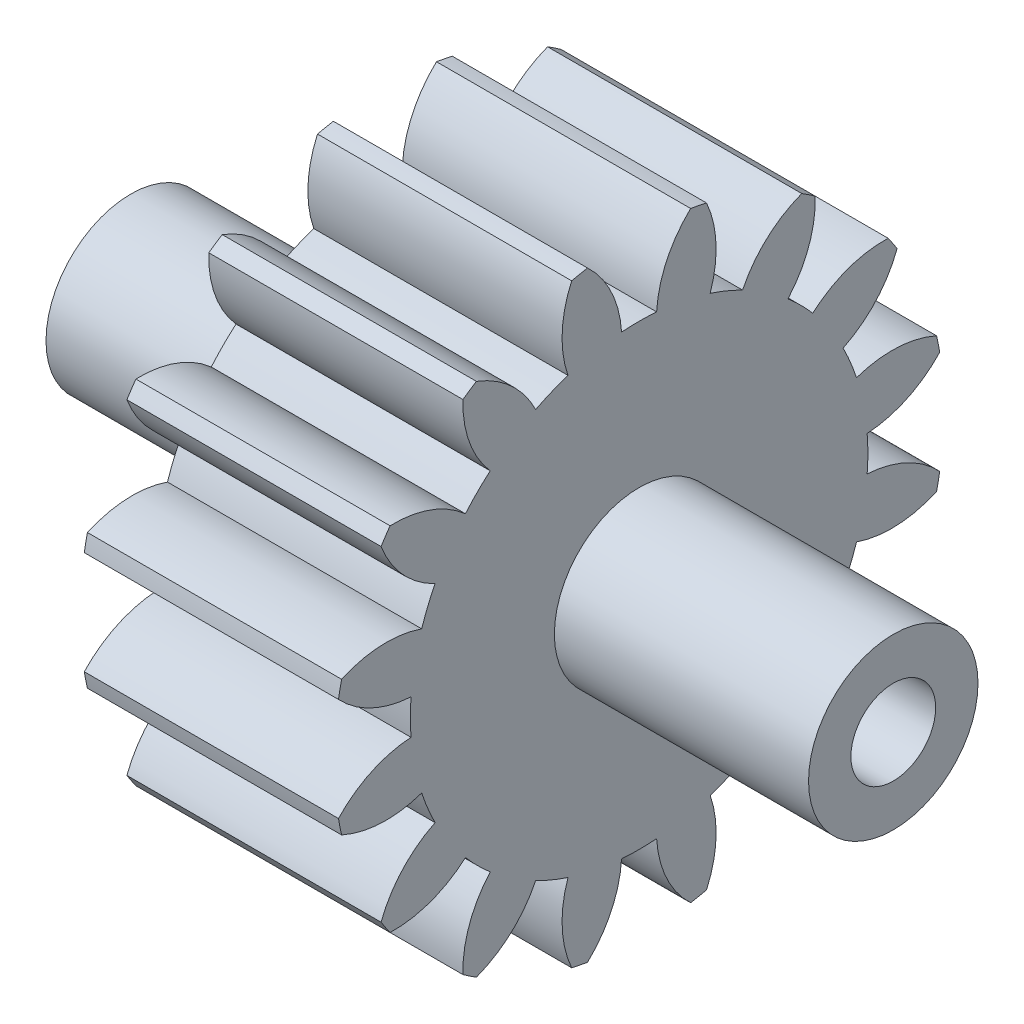
SolidWorks part; units mm, degrees
ref_plane "Plane1" through (0, 0, 0) normal (0, 0, 1) x (1, 0, 0)
ref_plane "Plane2" through (0, 0, 0) normal (0, 1, 0) x (1, 0, 0)
ref_plane "Plane3" through (0, 0, 0) normal (1, 0, 0) x (0, 0, -1)
other "Configuration Table"
sketch "HoldingSke" plane through (0, 0, 0) normal (0, 1, 0) x (1, 0, 0)
  line L0 (0, 0) -> (0.4806, -0.1378)
  line L1 (-15, 0) -> (100, 0) construction
  line L2 (0, 0) -> (-2.1039, 2.3779)
  line L3 (0, 0) -> (-11.863, 4.5341)
  line L4 (0, 0) -> (8.3015, 2.3804)
  line L5 (0, 0) -> (-42.1629, -15.7255)
  line L6 (0, 0) -> (-12.4344, -8.3896)
  line L7 (-2.1039, 2.3779) -> (7.5823, 46.3231)
  line L8 (-76.2, 54.61) -> (-75.3, 54.61)
  line L9 (-71.009, 38.7566) -> (-53.1078, 45.2721)
  line L10 (-76.2, 71.12) -> (104.1128, 71.12)
  line L11 (0, 0) -> (-15, 0)
  line L12 (-76.2, 101.6) -> (-76.133, 101.6)
  line L13 (24.9733, 27.94) -> (52.9518, 28.4284)
  line L14 (24.9733, 27.94) -> (24.9743, 27.94)
  line L15 (24.9733, 27.94) -> (100.4006, 29.5858)
  line L16 (-63.627, -2) -> (-12.827, -2)
  circle A0 centre (0, 0) radius 2.5
  circle A1 centre (0, 0) radius 5
  circle A2 centre (0, 0) radius 5
  circle A3 centre (0, 0) radius 2.5
  dimension "MHD" = 10
  dimension "Hub_dia" = 10
  dimension "Bore" = 5
  dimension "MBD" = 5
  dimension "Num_teeth" = 16
  dimension "Pitch" = 0.5
  dimension "Overall_len" = 45
  dimension "Show_teeth" = 16
  dimension "Thickness" = 15
  dimension "OAL" = 45.0001
  dimension "T_dim" = 0.9
  dimension "Ap" = 20
  dimension "H" = 19.05
  dimension "Pitch_radius" = 180.3128
  dimension "Width" = 15
  dimension "Backlash" = 0.067
  dimension "Addendum_fac" = 1
  dimension "Dedendum_fac" = 1.25
  dimension "Clearance_fac" = 0.25
  dimension "Dedendum_add" = 0.001
  dimension "Module" = 2
sketch "BasProSke" plane through (0, 0, 0) normal (0, 1, 0) x (1, 0, 0)
  line L0 (-10, 0) -> (60, 0) construction
  line L1 (0, 0) -> (0, 18)
  line L2 (0, 0) -> (15, 0)
  line L3 (15, 0) -> (15, 18)
  line L4 (15, 18) -> (0, 18)
  dimension "Thickness" = 15
  dimension "Diameter" = 36
revolve "Base-Revolve" add sketch "BasProSke" angle 360 about L0
sketch "TooCutSke" plane through (0, 0, 0) normal (1, 0, 0) x (0, 0, -1)
  line L1 (0, 0) -> (0, 107) construction
  line L2 (0, 0) -> (-1.6854, 15.911) construction
  line L3 (0, 0) -> (-6.2172, 31.2558) construction
  line L4 (-1.6854, 15.911) -> (-3.1086, 15.6279) construction
  arc A0 (1.0343, 13.4593) -> (-1.0343, 13.4593) centre (0, 0) ccw
  arc A1 (3.0657, 17.7628) -> (-3.0657, 17.7628) centre (0, 0) ccw
  circle A2 centre (0, 0) radius 16 construction
  circle A3 centre (0, 0) radius 15.0351 construction
  arc A4 (-1.0343, 13.4593) -> (-3.0657, 17.7628) centre (-7.4228, 13.075) ccw
  arc A5 (3.0657, 17.7628) -> (1.0343, 13.4593) centre (7.4228, 13.075) ccw
  dimension "Root_dia" = 26.998
  dimension "Overcut_dia" = 36.0508
  dimension "Pitch_dia" = 32
  dimension "Base_dia" = 30.0702
  dimension "Flank_rad" = 6.4
  dimension "Half_ang" = 11.25
  dimension "Half_CT" = 1.451
extrude "ToothCut" cut sketch "TooCutSke" along normal through all
fillet "Breaks" [suppressed] radius 0.04
fillet "RootFillets" [suppressed] radius 0.501
pattern_circular "TeethCuts" count 16 every 22.5 about axis through (-10, 0, 0) along (1, 0, 0) of "ToothCut", "RootFillets", "Breaks"
sketch "HubNeaOneSke" plane through (0, 0, 0) normal (-1, 0, 0) x (0, 0, 1)
  circle A0 centre (0, 0) radius 5
  dimension "Diameter" = 10
extrude "HubNearOne" [suppressed] add sketch "HubNeaOneSke" along normal blind 30.0001
sketch "HubNeaBotSke" plane through (0, 0, 0) normal (-1, 0, 0) x (0, 0, 1)
  circle A0 centre (0, 0) radius 5
  dimension "Diameter" = 10
extrude "HubNearBoth" add sketch "HubNeaBotSke" along normal blind 15
ref_plane "FarPln" through (15, 0, 0) normal (1, 0, 0) x (0, 0, -1)
sketch "HubFarSke" plane through (15, 0, 0) normal (1, 0, 0) x (0, 0, -1)
  circle A0 centre (0, 0) radius 5
  dimension "Diameter" = 10
extrude "HubFar" add sketch "HubFarSke" along normal blind 15
sketch "BorSke" plane through (0, 0, 0) normal (1, 0, 0) x (0, 0, -1)
  circle A0 centre (0, 0) radius 2.5
  dimension "Diameter" = 5
extrude "Bore" cut sketch "BorSke" along normal mid plane 90.0001
sketch "KeySke" plane through (0, 0, 0) normal (1, 0, 0) x (0, 0, -1)
  line L0 (-1, 0) -> (-1, 3.4)
  line L1 (-1, 3.4) -> (1, 3.4)
  line L2 (1, 3.4) -> (1, 0)
  line L3 (0, 0) -> (0, 34) construction
  line L4 (-1, 0) -> (1, 0)
  dimension "Offset" = 3.4
  dimension "Width" = 2
extrude "Keyway" [suppressed] cut sketch "KeySke" along normal mid plane 90.0001
pattern_circular "Keyway2" [suppressed] count 2 every 90 about axis through (-10, 0, 0) along (1, 0, 0)
equation "' \"Module@HoldingSke\" = 6.35"
equation "' \"Num_teeth@HoldingSke\" = 12"
equation "' \"Ap@HoldingSke\" =  20"
equation "' \"Ap@HoldingSke\" = 20"
equation "' \"Width@HoldingSke\" = 0.5 * 25.4"
equation "' \"Hub_dia@HoldingSke\"= 1 * 25.4"
equation "' \"Hub_dia@HoldingSke\" = 1 * 25.4"
equation "' \"Overall_len@HoldingSke\" = 1.0 * 25.4"
equation "' \"Bore@HoldingSke\" = 0.75 * 25.4"
equation "' \"T_dim@HoldingSke\" = 0.1 * 25.4"
equation "' \"Width@KeySke\" = 0.25 * 25.4"
equation "' \"Show_teeth@HoldingSke\" = 13"
equation "' \"Backlash@HoldingSke\" = 0.009 * 25.4"
equation "' \"Addendum_fac@HoldingSke\" = 1.0"
equation "' \"Dedendum_fac@HoldingSke\" = 1.25"
equation "' \"Dedendum_add@HoldingSke\" = 0.00005 * 25.4"
equation "' \"Clearance_fac@HoldingSke\" = 0.25"
equation "\"Pitch@HoldingSke\" = 1 / \"Module@HoldingSke\""
equation "\"Overcut_dia@TooCutSke\" = (\"Num_teeth@HoldingSke\" + 2 * \"Addendum_fac@HoldingSke\") / \"Pitch@HoldingSke\" + 0.002 * 25.4"
equation "\"Pitch_dia@TooCutSke\" = \"Num_teeth@HoldingSke\" / \"Pitch@HoldingSke\""
equation "\"Base_dia@TooCutSke\" = \"Num_teeth@HoldingSke\" / \"Pitch@HoldingSke\" * cos((\"Ap@HoldingSke\"  * 3.14159265 / 180))"
equation "\"Root_dia@TooCutSke\" = (\"Num_teeth@HoldingSke\" + 2) / \"Pitch@HoldingSke\" - 2 * (\"Addendum_fac@HoldingSke\" + \"Dedendum_fac@HoldingSke\") / \"Pitch@HoldingSke\" - \"Dedendum_add@HoldingSke\" * 2"
equation "\"Half_ang@TooCutSke\" = 180 / \"Num_teeth@HoldingSke\""
equation "\"Half_CT@TooCutSke\" = \"Num_teeth@HoldingSke\" / \"Pitch@HoldingSke\" * sin((3.14159265 / 2 / \"Num_teeth@HoldingSke\")) / 2 - 7 * \"Backlash@HoldingSke\" / 4"
equation "\"Flank_rad@TooCutSke\" = \"Num_teeth@HoldingSke\" / \"Pitch@HoldingSke\" / 5"
equation "\"Radius@RootFillets\" = \"Clearance_fac@HoldingSke\" / \"Pitch@HoldingSke\" + \"Dedendum_add@HoldingSke\""
equation "\"Break_rad@Breaks\" = 0.02 / \"Pitch@HoldingSke\""
equation "\"Thickness@HoldingSke\" = \"Width@HoldingSke\""
equation "\"OAL@HoldingSke\" = \"Thickness@HoldingSke\""
equation "\"MHD@HoldingSke\" = (\"Num_teeth@HoldingSke\" + 2) / \"Pitch@HoldingSke\" - 2 * (\"Addendum_fac@HoldingSke\" + \"Dedendum_fac@HoldingSke\")  / \"Pitch@HoldingSke\" - \"Dedendum_add@HoldingSke\" * 2"
equation "\"MBD@HoldingSke\" = (\"Num_teeth@HoldingSke\" + 2) / \"Pitch@HoldingSke\" - 2 * (\"Addendum_fac@HoldingSke\" + \"Dedendum_fac@HoldingSke\")  / \"Pitch@HoldingSke\" - \"Dedendum_add@HoldingSke\" * 2 - 0.002 * 25.4"
equation "\"MHD@HoldingSke\" = ((sgn( \"MHD@HoldingSke\" - \"Hub_dia@HoldingSke\" )-1)*( \"MHD@HoldingSke\" - \"Hub_dia@HoldingSke\" ))/-2+ \"Hub_dia@HoldingSke\""
equation "\"MBD@HoldingSke\" = ((sgn( \"MBD@HoldingSke\" - \"Bore@HoldingSke\" )-1)*( \"MBD@HoldingSke\" - \"Bore@HoldingSke\" ))/-2+ \"Bore@HoldingSke\""
equation "\"OAL@HoldingSke\" = ((sgn( \"OAL@HoldingSke\" - \"Overall_len@HoldingSke\" )+1)*( \"OAL@HoldingSke\" - \"Overall_len@HoldingSke\" ))/2 + \"Overall_len@HoldingSke\" + 0.000002 * 25.4"
equation "\"Num_teeth@TeethCuts\" = int( \"Show_teeth@HoldingSke\" ) + 1"
equation "\"Num_teeth@TeethCuts\" = ((sgn( \"Num_teeth@TeethCuts\" - \"Num_teeth@HoldingSke\" )-1)*( \"Num_teeth@TeethCuts\" - \"Num_teeth@HoldingSke\" ))/-2+ \"Num_teeth@HoldingSke\""
equation "\"Num_teeth@TeethCuts\" = ((sgn( \"Num_teeth@TeethCuts\" - 2.0)+1)*( \"Num_teeth@TeethCuts\" - 2.0))/2 +2.0"
equation "\"Angle@TeethCuts\" = 360.0 / \"Num_teeth@HoldingSke\""
equation "\"Diameter@BasProSke\" = (\"Num_teeth@HoldingSke\" + 2 * \"Addendum_fac@HoldingSke\") / \"Pitch@HoldingSke\""
equation "\"Thickness@BasProSke\"  = \"Thickness@HoldingSke\""
equation "' \"Fillet_rad@BasProSke\" =  \"Thickness@HoldingSke\" * 0.05"
equation "' \"Fillet_rad@BasProSke\" = \"Thickness@HoldingSke\" * 0.05"
equation "\"MHD@HoldingSke\" = ((sgn( \"MHD@HoldingSke\" - \"Root_dia@TooCutSke\" )-1)*( \"MHD@HoldingSke\" - \"Root_dia@TooCutSke\" ))/-2+ \"Root_dia@TooCutSke\""
equation "\"Diameter@HubNeaOneSke\" = \"MHD@HoldingSke\""
equation "\"Length@HubNearOne\" = \"OAL@HoldingSke\" - \"Thickness@BasProSke\""
equation "\"Diameter@HubNeaBotSke\" = \"MHD@HoldingSke\""
equation "\"Length@HubNearBoth\" = ( \"OAL@HoldingSke\" - \"Thickness@BasProSke\" ) / 2.0"
equation "\"Thickness@FarPln\" = \"Thickness@BasProSke\""
equation "\"Diameter@HubFarSke\" = \"MHD@HoldingSke\""
equation "\"Length@HubFar\" = ( \"OAL@HoldingSke\" - \"Thickness@BasProSke\" ) / 2.0"
equation "\"Diameter@BorSke\" = \"MBD@HoldingSke\""
equation "\"D1@Bore\" = \"OAL@HoldingSke\" * 2.0"
equation "\"D1@Keyway\" = \"OAL@HoldingSke\" * 2.0"
equation "\"Offset@KeySke\" = \"T_dim@HoldingSke\" + \"MBD@HoldingSke\" / 2.0"
